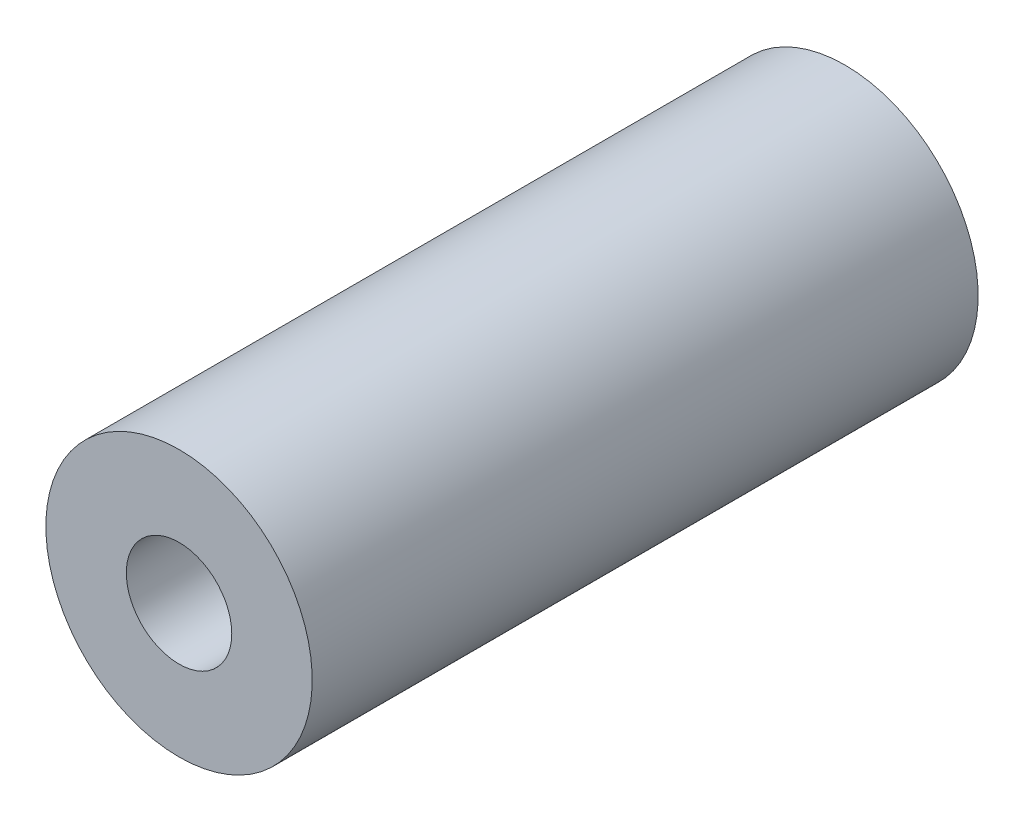
SolidWorks part; units mm, degrees
ref_plane "Plan de face" through (0, 0, 0) normal (0, 0, 1) x (1, 0, 0)
ref_plane "Plan de dessus" through (0, 0, 0) normal (0, 1, 0) x (1, 0, 0)
ref_plane "Plan de droite" through (0, 0, 0) normal (1, 0, 0) x (0, 0, -1)
sketch "Esquisse1" plane through (0, 0, 0) normal (1, 0, 0) x (0, 0, -1)
  line L0 (0, 0) -> (0, -6)
  line L6 (30, -6) -> (30, 0)
  line L7 (30, 0) -> (0, 0)
  line L8 (0, -6) -> (30, -6)
  dimension "D1" = 30
  dimension "D4" = 6
revolve "Révolution1" add sketch "Esquisse1" angle 360 about L7
sketch "Esquisse2" plane through (0, 0, 0) normal (0, 0, 1) x (1, 0, 0)
  line L0 (0, 0) -> (0, 1.5) construction
  line L1 (0, 0) -> (0, -2.375) construction
  line L2 (0, 1.5) -> (1.8414, 1.5)
  line L3 (0, 1.5) -> (-1.8414, 1.5)
  circle A0 centre (0, 0) radius 2.375
  dimension "D1" = 4.75
  dimension "D2" = 1.5
sketch "Esquisse3" plane through (0, 0, -30) normal (0, 0, -1) x (-1, 0, 0)
  circle A0 centre (0, 0) radius 4.5
  dimension "D1" = 9
extrude "Enlèv. mat.-Extru.4" cut sketch "Esquisse2" against normal blind 7.5 contours L2 A0 L3
sketch "Esquisse5" plane through (0, 0, 0) normal (0, 0, 1) x (1, 0, 0)
  line L0 (-1.8414, 1.5) -> (1.8414, 1.5)
  circle A0 centre (0, 0) radius 2.375
  arc A1 (-1.8414, 1.5) -> (1.8414, 1.5) centre (0, 0) ccw
  line M3 (1.8414, 1.5) -> (-1.8414, 1.5)
  dimension "D1" = 4.75
extrude "Enlèv. mat.-Extru.5" cut sketch "Esquisse5" against normal blind 15 contours A0 M3
extrude "Enlèv. mat.-Extru.6" cut sketch "Esquisse3" against normal blind 10
sketch "Esquisse7" plane through (0, 0, -20) normal (0, 0, -1) x (-1, 0, 0)
  line L2 (0, -4.5) -> (0, 2.5) construction
  line L5 (0, 2.5) -> (3.7417, 2.5)
  line L6 (0, 2.5) -> (-3.7417, 2.5)
  circle A3 centre (0, 0) radius 4.5 construction
  arc A4 (-3.7417, 2.5) -> (3.7417, 2.5) centre (0, 0) ccw
  dimension "D1" = 7
extrude "Enlèv. mat.-Extru.9" cut sketch "Esquisse7" against normal blind 5
